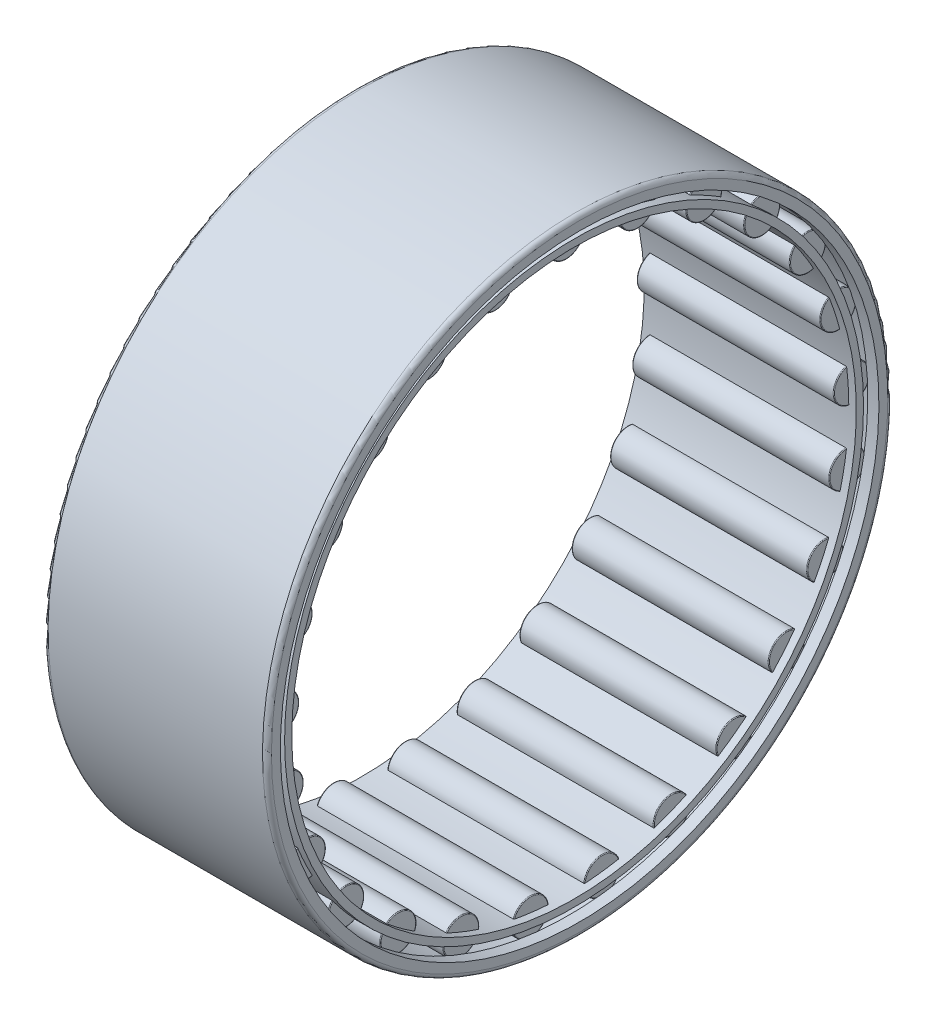
SolidWorks part; units mm, degrees
ref_plane "Plane1" through (0, 0, 0) normal (0, 0, 1) x (1, 0, 0)
ref_plane "Plane2" through (0, 0, 0) normal (0, 1, 0) x (1, 0, 0)
ref_plane "Plane3" through (0, 0, 0) normal (1, 0, 0) x (0, 0, -1)
sketch "Clipboard" plane through (0, 0, 0) normal (0, 0, 1) x (1, 0, 0)
  line L0 (-10, 0) -> (10, 0) construction
  line L1 (0, 0) -> (20.2657, -9.45)
  line L2 (0, 0) -> (36.8323, 17.1752)
  line L3 (0, 0) -> (20.2657, -9.45)
  line L4 (0, 0) -> (-76.2, -2.661)
  dimension "BallCLRad" = 40.64
  dimension "Count" = 25
  dimension "Show_count" = 25
  dimension "Max_count" = 25
  dimension "Min_count" = 2
  dimension "Bore" = 76.2
sketch "InnRacSke" plane through (0, 0, 0) normal (0, 0, 1) x (1, 0, 0)
  line L0 (-14.2875, 42.545) -> (-15.875, 42.545)
  line L1 (-15.875, 42.545) -> (-15.875, 43.815)
  line L2 (-15.24, 44.45) -> (15.24, 44.45)
  line L4 (15.875, 43.815) -> (15.875, 42.545)
  line L5 (15.875, 42.545) -> (14.2875, 42.545)
  line L6 (14.2875, 42.545) -> (14.2875, 43.18)
  line L7 (14.2875, 43.18) -> (-14.2875, 43.18)
  line L8 (-14.2875, 43.18) -> (-14.2875, 42.545)
  line L9 (-31.75, 0) -> (31.75, 0) construction
  arc A0 (-15.875, 43.815) -> (-15.24, 44.45) centre (-15.24, 43.815) cw
  arc A2 (15.24, 44.45) -> (15.875, 43.815) centre (15.24, 43.815) cw
  dimension "radius" = 0.635
  dimension "D1" = 86.36
  dimension "OD" = 88.9
  dimension "Width" = 31.75
  dimension "groove_dp" = 0.635
  dimension "Cyl_Len" = 28.575
  dimension "halfCyl" = 14.2875
revolve "Race" add sketch "InnRacSke" angle 360 about L9
sketch "RolDetSke" plane through (0, 0, 0) normal (0, 0, 1) x (1, 0, 0)
  line L0 (-14.0018, 43.0906) -> (-14.0017, 40.64)
  line L1 (-14.0017, 40.64) -> (14.0017, 40.64)
  line L2 (14.0017, 40.64) -> (14.0018, 43.0906)
  line L3 (13.8996, 43.1927) -> (-13.8996, 43.1927)
  line L4 (-28.575, 40.64) -> (28.575, 40.64) construction
  arc A0 (14.0018, 43.0906) -> (13.8996, 43.1927) centre (13.8996, 43.0906) ccw
  arc A1 (-13.8996, 43.1927) -> (-14.0018, 43.0906) centre (-13.8996, 43.0906) ccw
  dimension "Roller_radius" = 0.1021
  dimension "Roller_diameter" = 5.1054
  dimension "Roller_length" = 28.0035
  dimension "RollerCLRad" = 40.64
  dimension "halfLength" = 14.0017
revolve "RollerDetailed" add sketch "RolDetSke" angle 360 about L4
ref_axis "Axis1" through (-50, 0, 0) along (1, 0, 0)
sketch "CagSpiSke" plane through (0, 0, 0) normal (0, 0, 1) x (1, 0, 0)
  line L0 (15.0812, 40.1295) -> (15.0812, 41.1505)
  line L1 (15.0812, 41.1505) -> (-15.0813, 41.1505)
  line L2 (-15.0813, 41.1505) -> (-15.0813, 40.1295)
  line L3 (-15.0813, 40.1295) -> (15.0812, 40.1295)
  line L4 (-31.75, 0) -> (31.75, 0) construction
  dimension "Cage_width" = 30.1625
  dimension "D2" = 80.2589
  dimension "Cage_thickness" = 1.0211
  dimension "halfWidth" = 15.0812
revolve "CageSpine" add sketch "CagSpiSke" angle 360 about L4
pattern_circular "RollersDetailed" count 25 every 14.4 about axis through (-50, 0, 0) along (1, 0, 0) of "RollerDetailed"
sketch "RolSimSke" plane through (0, 0, 0) normal (0, 0, 1) x (1, 0, 0)
  line L0 (-25.4, 0) -> (25.4, 0) construction
  line L2 (-13.8996, 43.2054) -> (13.8996, 43.2054)
  line L3 (-14.0018, 43.1033) -> (-14.0018, 38.2021)
  line L4 (-13.8996, 38.1) -> (13.8996, 38.1)
  line L5 (14.0017, 43.1033) -> (14.0017, 38.2021)
  arc A0 (-14.0018, 38.2021) -> (-13.8996, 38.1) centre (-13.8996, 38.2021) ccw
  arc A1 (-13.8996, 43.2054) -> (-14.0018, 43.1033) centre (-13.8996, 43.1033) ccw
  arc A2 (14.0017, 43.1033) -> (13.8996, 43.2054) centre (13.8996, 43.1033) ccw
  arc A3 (13.8996, 38.1) -> (14.0017, 38.2021) centre (13.8996, 38.2021) ccw
  point P10 (-14.0018, 38.1)
  point P15 (14.0017, 43.2054)
  point P18 (14.0017, 38.1)
  dimension "Bore" = 76.2
  dimension "Roller_diameter" = 5.1054
  dimension "Roller_length" = 28.0035
  dimension "D1" = 0.1021
  dimension "halfWidth" = 14.0017
revolve "RollersSimplified" [suppressed] add sketch "RolSimSke" angle 360 about L0
equation "\"BallCLRad@Clipboard\" =  ( \"D1@InnRacSke\" + \"Bore@Clipboard\" )  / 4"
equation "\"RollerCLRad@RolDetSke\" = \"BallCLRad@Clipboard\""
equation "\"halfCyl@InnRacSke\" = \"Cyl_Len@InnRacSke\" / 2"
equation "\"Roller_length@RolDetSke\" = \"Cyl_Len@InnRacSke\" * .98"
equation "\"halfLength@RolDetSke\" = \"Roller_length@RolDetSke\" / 2"
equation "\"Roller_diameter@RolDetSke\" =  ( \"D1@InnRacSke\" - \"Bore@Clipboard\" )  / 2 + .001"
equation "\"Roller_radius@RolDetSke\" = \"Roller_diameter@RolDetSke\" / 50"
equation "\"Cage_width@CagSpiSke\" =  ( \"Cyl_Len@InnRacSke\" + \"Width@InnRacSke\" )  / 2"
equation "\"halfWidth@CagSpiSke\" = \"Cage_width@CagSpiSke\" / 2"
equation "\"Cage_thickness@CagSpiSke\"  = \"Roller_diameter@RolDetSke\" / 5"
equation "\"D2@CagSpiSke\" =  \"RollerCLRad@RolDetSke\" * 2 - \"Cage_thickness@CagSpiSke\""
equation "\"Roller_length@RolSimSke\" = \"Cyl_Len@InnRacSke\" * .98"
equation "\"halfWidth@RolSimSke\" = \"Roller_length@RolSimSke\" / 2"
equation "\"D1@RolSimSke\" = \"Roller_radius@RolDetSke\""
equation "\"Roller_diameter@RolSimSke\" =  ( \"D1@InnRacSke\" - \"Bore@Clipboard\" )  / 2 + .001"
equation "\"Bore@RolSimSke\" = \"Bore@Clipboard\""
equation "\"Max_count@Clipboard\" = int( 3.14159265 / atn(( \"Roller_diameter@RolDetSke\" / 2) / sqr( \"RollerCLRad@RolDetSke\"  *  \"RollerCLRad@RolDetSke\" - ( \"Roller_diameter@RolDetSke\" / 2) *  ( \"Roller_diameter@RolDetSke\" / 2))))"
equation "\"Max_count@Clipboard\" = ((sgn( \"Max_count@Clipboard\" - \"Count@Clipboard\" )-1)*( \"Max_count@Clipboard\" - \"Count@Clipboard\" ))/-2+ \"Count@Clipboard\""
equation "\"Count@RollersDetailed\" = int( \"Show_count@Clipboard\" ) "
equation "\"Count@RollersDetailed\" = ((sgn( \"Count@RollersDetailed\" - \"Max_count@Clipboard\" )-1)*( \"Count@RollersDetailed\" - \"Max_count@Clipboard\" ))/-2+ \"Max_count@Clipboard\""
equation "\"Count@RollersDetailed\" = ((sgn( \"Count@RollersDetailed\" - \"Min_count@Clipboard\" )+1)*( \"Count@RollersDetailed\" - \"Min_count@Clipboard\"))/2 +\"Min_count@Clipboard\""
equation "\"Angle@RollersDetailed\" = 360.0 / \"Max_count@Clipboard\""
equation "\"Angle@CageSpine\" =  \"Angle@RollersDetailed\" * ( \"Count@RollersDetailed\" -1 + int( \"Count@RollersDetailed\" / \"Max_count@Clipboard\" ) )  + 0.001 -  int( \"Count@RollersDetailed\" / \"Max_count@Clipboard\" ) * 0.001"
equation "\"Angle@CageSpine\" =  \"Angle@CageSpine\" * int( \"Min_count@Clipboard\" / 2) + int(1 / \"Min_count@Clipboard\")  * 0.001"
